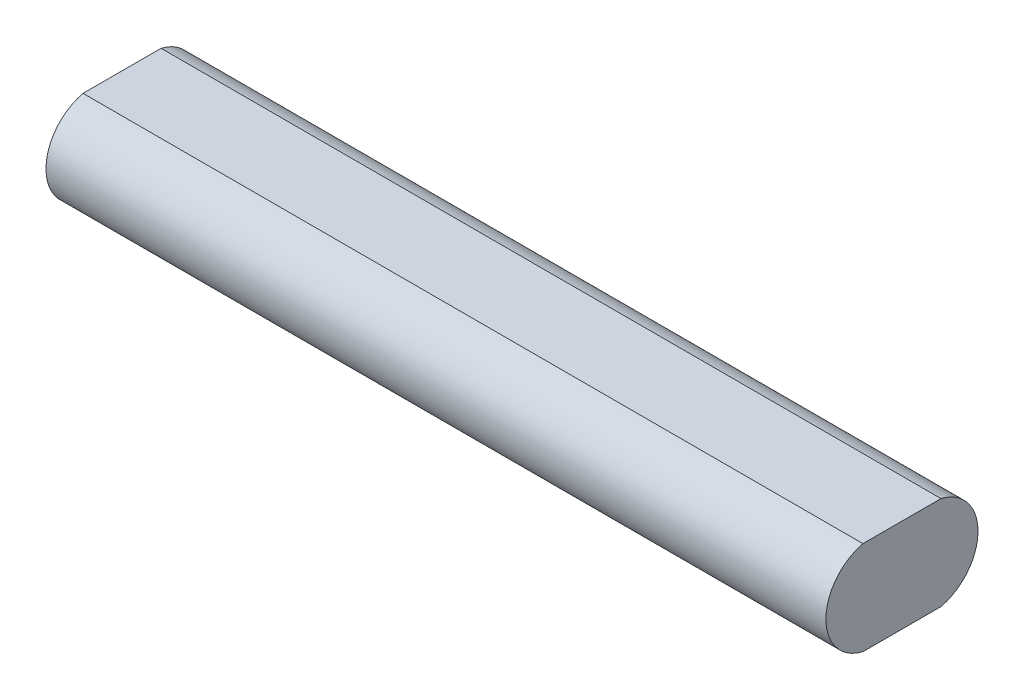
SolidWorks part; units mm, degrees
ref_plane "Front Plane" through (0, 0, 0) normal (0, 0, 1) x (1, 0, 0)
ref_plane "Top Plane" through (0, 0, 0) normal (0, 1, 0) x (1, 0, 0)
ref_plane "Right Plane" through (0, 0, 0) normal (1, 0, 0) x (0, 0, -1)
sketch "Sketch1" plane through (0, 0, 0) normal (0, 1, 0) x (1, 0, 0)
  line L1 (20, 4) -> (-20, 4)
  line L2 (20, 4) -> (20, -4)
  line L3 (20, -4) -> (-20, -4)
  line L4 (-20, 4) -> (-20, -4)
  line L5 (20, 4) -> (-20, -4) construction
  line L6 (20, -4) -> (-20, 4) construction
  point P0 (0, 0)
  dimension "D1" = 40
  dimension "D2" = 8
extrude "Boss-Extrude1" add sketch "Sketch1" along normal blind 4.8 contours L2 L1 L4 L3
sketch "Sketch2" plane through (20, 0, 0) normal (1, 0, 0) x (0, 0, -1)
  line L0 (-4, 0) -> (-2.0014, 0) construction
  line L1 (4, 0) -> (-4, 0) construction
  line L2 (-4, 2.4) -> (-3.9, 2.4) construction
  line L3 (-4, 4.8) -> (-4, 0) construction
  line L4 (4, 4.8) -> (-4, 4.8) construction
  line L5 (-2.0014, 4.8) -> (-4, 4.8)
  line L6 (-4, 4.8) -> (-4, 0)
  line L7 (-4, 0) -> (-2.0014, 0)
  line L8 (0, 4.8) -> (0, 0) construction
  line L9 (4, 4.8) -> (4, 0)
  line L10 (2.0014, 4.8) -> (4, 4.8)
  line L11 (4, 0) -> (2.0014, 0)
  arc A0 (-2.0014, 0) -> (-2.0014, 4.8) centre (-1.4338, 2.4) cw
  arc A1 (2.0014, 0) -> (2.0014, 4.8) centre (1.4338, 2.4) ccw
  point P8 (-3.9, 2.4)
  dimension "D1" = 0.1
extrude "Cut-Extrude1" cut sketch "Sketch2" against normal through all contours L9 L11 A1 L10 | L7 A0 L5 L6
